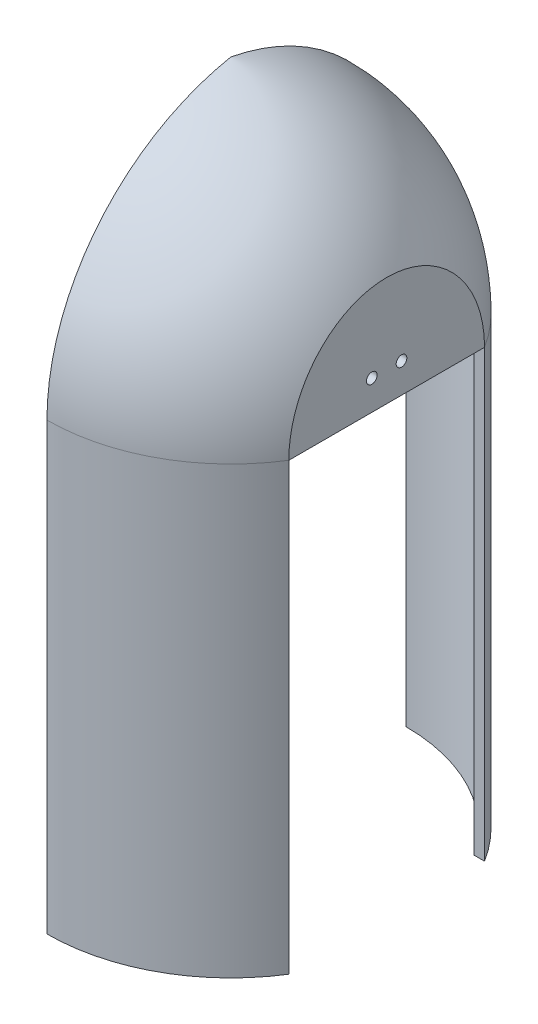
SolidWorks part; units mm, degrees
ref_plane "Front Plane" through (0, 0, 0) normal (0, 0, 1) x (1, 0, 0)
ref_plane "Top Plane" through (0, 0, 0) normal (0, 1, 0) x (1, 0, 0)
ref_plane "Right Plane" through (0, 0, 0) normal (1, 0, 0) x (0, 0, -1)
sketch "Sketch1" plane through (0, 0, 0) normal (0, 0, 1) x (1, 0, 0)
  line L0 (62, 0) -> (59, 0)
  line L2 (0, 75) -> (0, 71.9432)
  arc A0 (62, 0) -> (0, 75) centre (-14.3629, 0) ccw
  arc A1 (59, 0) -> (0, 71.9432) centre (-14.3629, 0) ccw
  arc A2 (59, 0) -> (-0.5643, 72.0535) centre (-14.3629, 0) ccw construction
  dimension "D1" = 3
  dimension "D2" = 62
  dimension "D3" = 75
revolve "Revolve1" add sketch "Sketch1" angle 360 about L2
sketch "Sketch2" plane through (0, 0, 0) normal (0, -1, 0) x (-1, 0, 0)
  line L1 (52.5, 72.8837) -> (-52.5, 72.8837)
  line L2 (52.5, 72.8837) -> (52.5, -72.8837)
  line L3 (52.5, -72.8837) -> (-52.5, -72.8837)
  line L4 (-52.5, 72.8837) -> (-52.5, -72.8837)
  line L5 (52.5, 72.8837) -> (-52.5, -72.8837) construction
  line L6 (52.5, -72.8837) -> (-52.5, 72.8837) construction
  point P0 (0, 0)
  dimension "D1" = 105
  dimension "D2" = 145.7674
extrude "Cut-Extrude2" cut sketch "Sketch2" against normal through all flip side to cut
sketch "Sketch3" plane through (0, 0, 0) normal (0, -1, 0) x (1, 0, 0)
  line L0 (-52.5, 32.9811) -> (-48.9209, 32.9811)
  line L1 (-48.9209, 32.9811) -> (-48.9209, -32.9811)
  line L2 (-48.9209, -32.9811) -> (-52.5, -32.9811)
  line L3 (-52.5, -32.9811) -> (-52.5, 32.9811)
  line L4 (0, 0) -> (0, 17.4115) construction
  line L5 (48.9209, -32.9811) -> (52.5, -32.9811)
  line L6 (52.5, 32.9811) -> (48.9209, 32.9811)
  line L7 (52.5, -32.9811) -> (52.5, 32.9811)
  line L8 (48.9209, 32.9811) -> (48.9209, -32.9811)
  arc A0 (52.5, 26.9212) -> (-52.5, 26.9212) centre (0, 0) ccw construction
  arc A1 (-52.5, -26.9212) -> (52.5, -26.9212) centre (0, 0) ccw construction
extrude "Boss-Extrude2" add sketch "Sketch3" against normal up to surface
sketch "Sketch4" plane through (0, 0, 0) normal (0, -1, 0) x (-1, 0, 0)
  line L0 (52.5007, -32.98) -> (48.9216, -32.98)
  line L2 (-48.9216, -32.98) -> (-52.5007, -32.98)
  line L3 (0, 0) -> (-30.1101, 0) construction
  line L5 (-48.9216, 32.98) -> (-52.5007, 32.98)
  line L6 (52.5007, 32.98) -> (48.9216, 32.98)
  arc A1 (-48.9216, -32.98) -> (48.9216, -32.98) centre (0, 0) ccw
  arc A2 (-52.5007, -32.98) -> (52.5007, -32.98) centre (0, 0) ccw
  arc A3 (-49.9603, -31.3842) -> (49.9603, -31.3842) centre (0, 0) ccw construction
  arc A4 (-52.5007, 32.98) -> (52.5007, 32.98) centre (0, 0) cw
  arc A5 (-48.9216, 32.98) -> (48.9216, 32.98) centre (0, 0) cw
  dimension "D2" = 62
  dimension "D3" = 32.98
  dimension "D1" = 3
extrude "Boss-Extrude4" add sketch "Sketch4" along normal blind 150
sketch "Sketch5" plane through (0, 0, 0) normal (0, 0, 1) x (1, 0, 0)
  line L1 (0, 81.3691) -> (-112.5201, 81.3691)
  line L2 (0, 81.3691) -> (0, -154.2705)
  line L3 (0, -154.2705) -> (-112.5201, -154.2705)
  line L4 (-112.5201, 81.3691) -> (-112.5201, -154.2705)
extrude "Cut-Extrude3" cut sketch "Sketch5" against normal through all both and the other way through all
sketch "Sketch6" plane through (52.5, 0, 0) normal (1, 0, 0) x (0, 0, -1)
  line L0 (0, 0) -> (0, 16.2755) construction
  line L1 (-32.98, 0) -> (32.98, 0) construction
  circle A0 centre (-5, 10) radius 1.8
  circle A1 centre (5, 10) radius 1.8
  point P8 (0, 0)
  dimension "D1" = 3.6
  dimension "D2" = 10
  dimension "D3" = 10
extrude "Cut-Extrude4" cut sketch "Sketch6" against normal through all both and the other way through all
